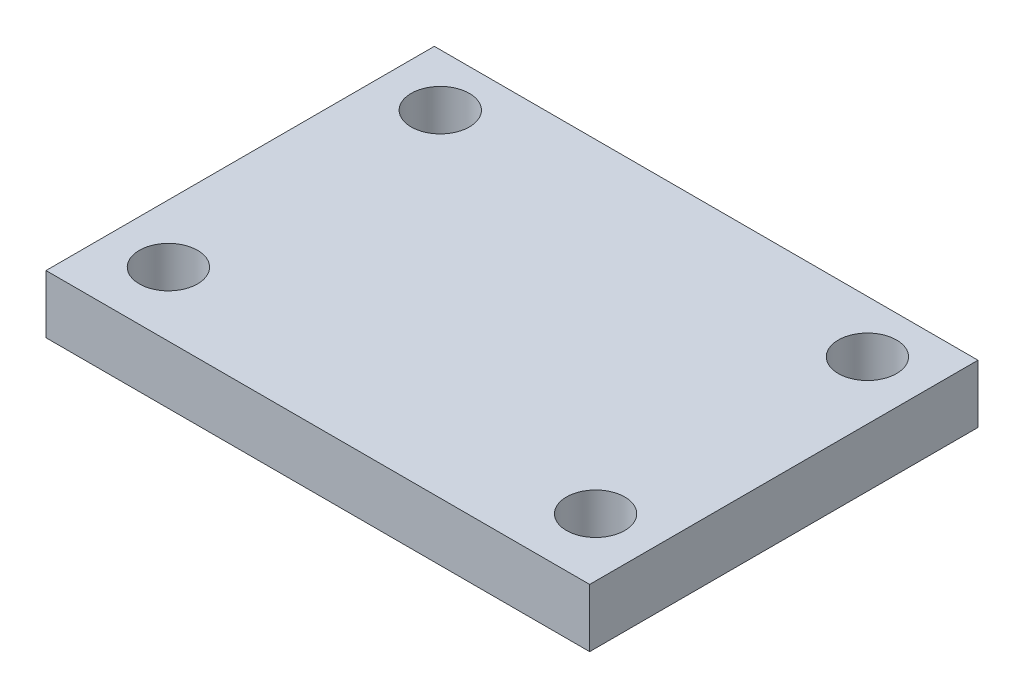
SolidWorks part; units mm, degrees
ref_plane "Front Plane" through (0, 0, 0) normal (0, 0, 1) x (1, 0, 0)
ref_plane "Top Plane" through (0, 0, 0) normal (0, 1, 0) x (1, 0, 0)
ref_plane "Right Plane" through (0, 0, 0) normal (1, 0, 0) x (0, 0, -1)
sketch "Sketch1" plane through (0, 0, 0) normal (0, 1, 0) x (1, 0, 0)
  line L0 (0, 11.4763) -> (0, -12.1139) construction
  line L1 (-14, 10) -> (14, 10)
  line L2 (-14, 10) -> (-14, -10)
  line L3 (-14, -10) -> (14, -10)
  line L4 (14, 10) -> (14, -10)
  line L5 (-14, 10) -> (14, -10) construction
  line L6 (-14, -10) -> (14, 10) construction
  line L7 (-16.8691, -0.3188) -> (18.2505, -0.3188) construction
  point P0 (0, 0)
  point P10 (-11, 7.3055)
  point P11 (-11, -6.6945)
  point P12 (11, -6.6945)
  point P13 (11, 7.3055)
  point P14 (0, 0)
  point P15 (0, 0)
  point P16 (-11, 6.7476)
  dimension "D3" = 3
  dimension "D1" = 28
  dimension "D2" = 20
  dimension "D4" = 3
  dimension "D5" = 3
  dimension "D6" = 3
  dimension "D7" = 14
  dimension "D8" = 22
  dimension "D9" = 14
extrude "Boss-Extrude1" add sketch "Sketch1" along normal blind 3
hole_wizard "Ø3.0 (3) Diameter Hole1" positions "Sketch3" profile "Sketch4" hole size "Ø3.0" standard "ISO" end condition through all
sketch "Sketch3" plane through (0, 0, 0) normal (0, -1, 0) x (-1, 0, 0)
  point P0 (-11, 7.3055)
  point P3 (11, 7.3055)
  point P6 (11, -6.6945)
  point P9 (-11, -6.6945)
sketch "Sketch4" plane through (11, 0, -7.3055) normal (1, 0, 0) x (0, 0, -1)
  line L0 (0, 0) -> (0, 3)
  line L1 (0, 3) -> (1.5, 3)
  line L2 (1.5, 3) -> (1.5, 0)
  line L5 (1.5, 0) -> (0, 0)
  line L11 (0, -6.35) -> (0, 107.95) construction
  dimension "Thru Hole Dia." = 3
  dimension "Thru Hole Depth" = 3
